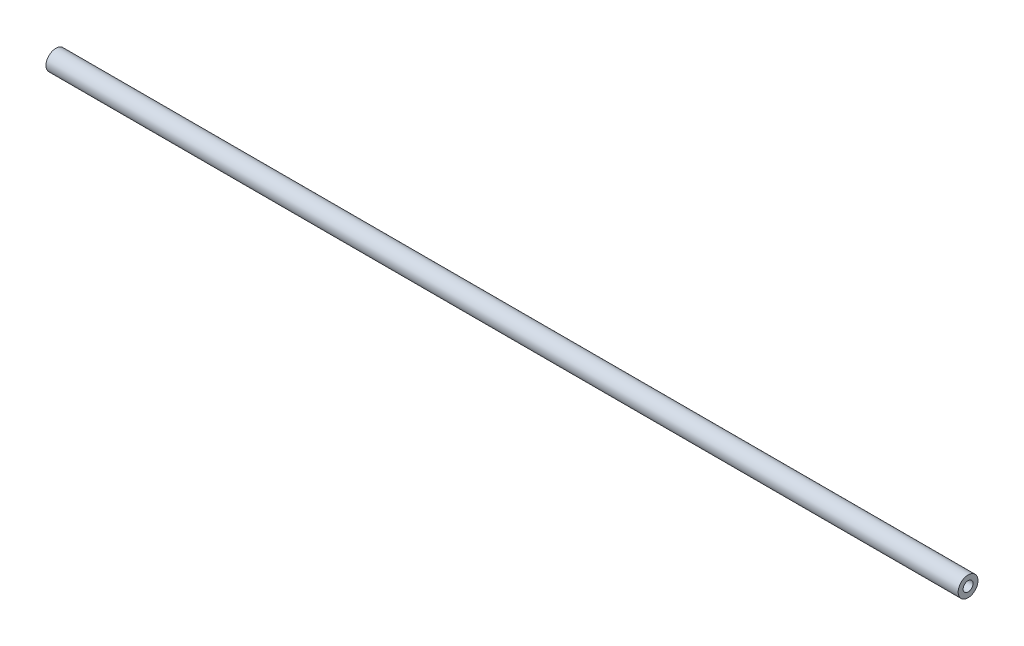
SolidWorks part; units mm, degrees
ref_plane "Front Plane" through (0, 0, 0) normal (0, 0, 1) x (1, 0, 0)
ref_plane "Top Plane" through (0, 0, 0) normal (0, 1, 0) x (1, 0, 0)
ref_plane "Right Plane" through (0, 0, 0) normal (1, 0, 0) x (0, 0, -1)
sketch "Sketch1" plane through (0, 0, 0) normal (1, 0, 0) x (0, 0, -1)
  circle A0 centre (0, 0) radius 1.5875
  circle A1 centre (0, 0) radius 0.7937
  dimension "D1" = 3.175
  dimension "D2" = 1.5875
extrude "Boss-Extrude1" add sketch "Sketch1" along normal blind 146.05
